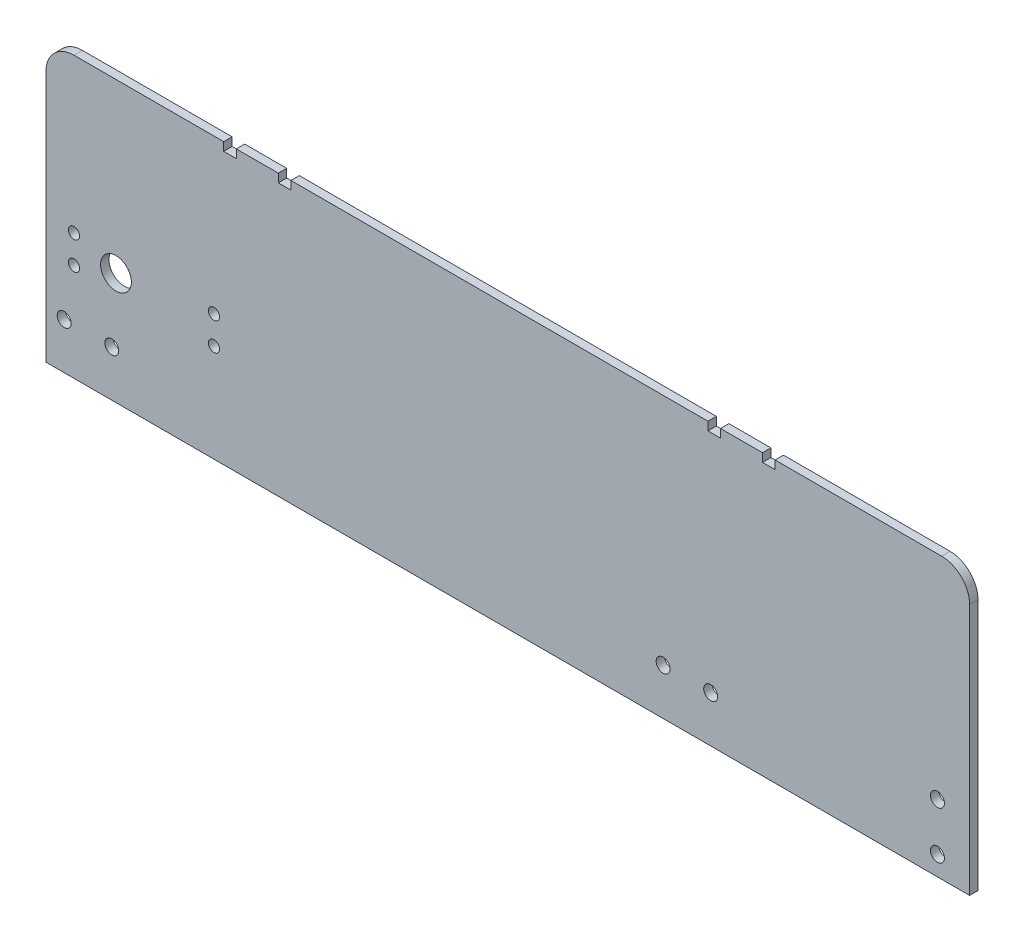
SolidWorks part; units mm, degrees
ref_plane "前视基准面" through (0, 0, 0) normal (0, 0, 1) x (1, 0, 0)
ref_plane "上视基准面" through (0, 0, 0) normal (0, 1, 0) x (1, 0, 0)
ref_plane "右视基准面" through (0, 0, 0) normal (1, 0, 0) x (0, 0, -1)
sketch "草图2" plane through (0, 0, 0) normal (0, 0, 1) x (1, 0, 0)
  line L0 (120, 0) -> (207, 0)
  line L1 (0, 0) -> (30, 0)
  line L2 (0, 0) -> (0, 90)
  line L3 (10, 100) -> (320, 100)
  line L4 (330, 0) -> (330, 90)
  line L9 (10, 45) -> (10, 35) construction
  line L10 (10, 40) -> (40, 40) construction
  line L11 (15, 0) -> (15, 21.8007) construction
  line L12 (30, 0) -> (120, 0)
  line L16 (208.9993, 0) -> (330, 0)
  line L17 (207, 0) -> (208.9993, 0)
  arc A2 (330, 90) -> (320, 100) centre (320, 90) ccw
  arc A3 (10, 100) -> (0, 90) centre (10, 90) ccw
  circle A4 centre (10, 45) radius 2
  circle A5 centre (10, 35) radius 2
  circle A6 centre (60, 45) radius 2
  circle A7 centre (60, 35) radius 2
  circle A8 centre (25, 40) radius 5.5
  circle A9 centre (6.5, 16.5) radius 2.5
  circle A10 centre (23.5, 16.5) radius 2.5
  circle A11 centre (220.5, 16.5) radius 2.5
  circle A12 centre (237.5, 16.5) radius 2.5
  point P11 (120, 15)
  point P18 (0, 100)
  dimension "D7" = 10
  dimension "D8" = 4
  dimension "D11" = 15
  dimension "D12" = 11
  dimension "D15" = 5
  dimension "D16" = 16.5
  dimension "D18" = 5
  dimension "D19" = 5
  dimension "D1" = 330
  dimension "D2" = 100
  dimension "D3" = 220.5
  dimension "D5" = 15
  dimension "D9" = 50
  dimension "D10" = 10
  dimension "D13" = 35
  dimension "D14" = 25
  dimension "D17" = 17
  dimension "D20" = 17
  dimension "D21" = 16.5
extrude "凸台-拉伸1" add sketch "草图2" along normal mid plane 3
sketch "草图3" plane through (0, 0, 1.5) normal (0, 0, 1) x (1, 0, 0)
  line L0 (0, 0) -> (330, 0) construction
  line L1 (330, 0) -> (330, 90) construction
  line L2 (318.5, 30.3329) -> (318.5, 1.5178) construction
  circle A0 centre (318.5, 24) radius 2.5
  circle A1 centre (318.5, 7) radius 2.5
  dimension "D1" = 5
  dimension "D2" = 17
  dimension "D3" = 7
  dimension "D4" = 11.5
extrude "切除-拉伸1" cut sketch "草图3" against normal blind 10
sketch "草图4" plane through (0, 0, 1.5) normal (0, 0, 1) x (1, 0, 0)
  line L0 (320, 100) -> (10, 100) construction
  line L1 (63.5, 100) -> (68, 100)
  line L2 (63.5, 100) -> (63.5, 97)
  line L3 (63.5, 97) -> (68, 97)
  line L4 (68, 100) -> (68, 97)
  line L5 (0, 90) -> (0, 0) construction
  line L6 (256, 100) -> (260.5, 100)
  line L7 (256, 100) -> (256, 97)
  line L8 (256, 97) -> (260.5, 97)
  line L9 (260.5, 100) -> (260.5, 97)
  dimension "D1" = 63.5
  dimension "D2" = 4.5
  dimension "D3" = 3
  dimension "D4" = 188
  dimension "D5" = 4.5
  dimension "D6" = 3
extrude "切除-拉伸2" cut sketch "草图4" against normal blind 10
sketch "草图5" plane through (0, 0, 1.5) normal (0, 0, 1) x (1, 0, 0)
  line L0 (256, 100) -> (68, 100) construction
  line L1 (83, 100) -> (87.5, 100)
  line L2 (83, 100) -> (83, 97)
  line L3 (83, 97) -> (87.5, 97)
  line L4 (87.5, 100) -> (87.5, 97)
  line L6 (68, 97) -> (68, 100) construction
  line L7 (256, 100) -> (256, 97) construction
  line L8 (236.5, 100) -> (241, 100)
  line L9 (236.5, 100) -> (236.5, 97)
  line L10 (236.5, 97) -> (241, 97)
  line L11 (241, 100) -> (241, 97)
  dimension "D1" = 4.5
  dimension "D2" = 3
  dimension "D3" = 15
  dimension "D4" = 4.5
  dimension "D5" = 3
  dimension "D6" = 15
extrude "切除-拉伸3" cut sketch "草图5" against normal blind 10
